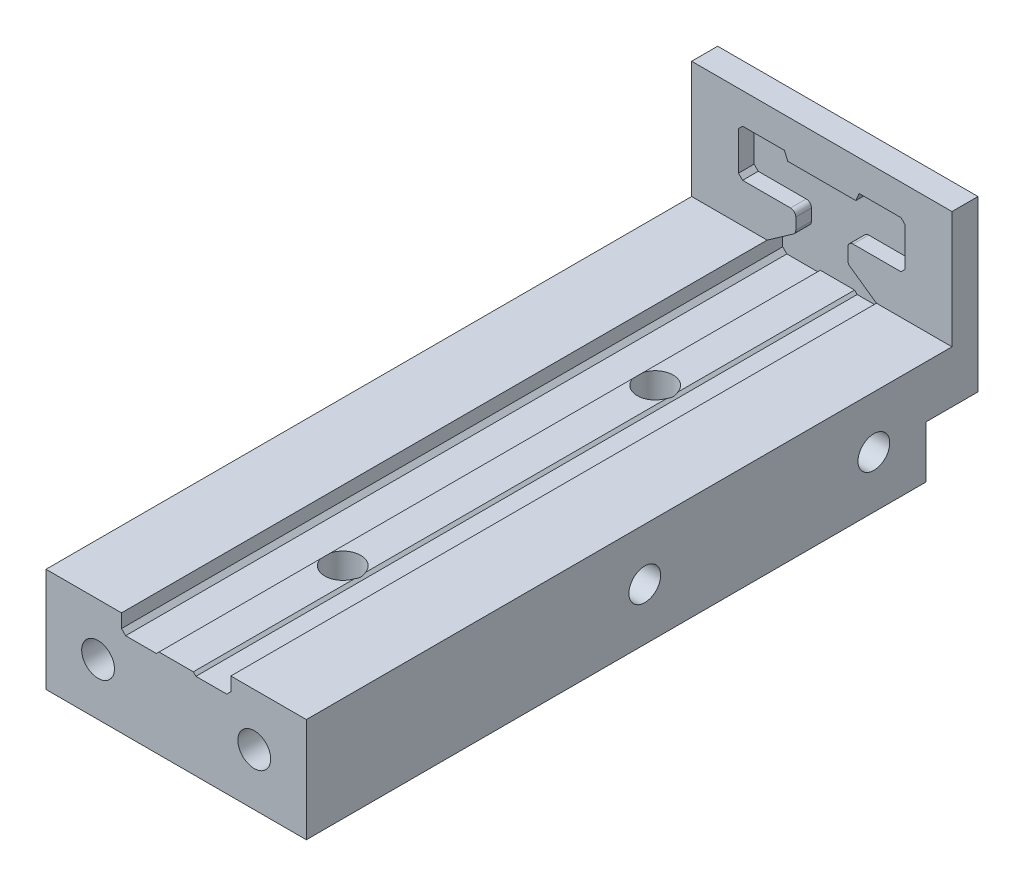
SolidWorks part; units mm, degrees
material "ABS"
ref_plane "Front Plane" through (0, 0, 0) normal (0, 0, 1) x (1, 0, 0)
ref_plane "Top Plane" through (0, 0, 0) normal (0, 1, 0) x (1, 0, 0)
ref_plane "Right Plane" through (0, 0, 0) normal (1, 0, 0) x (0, 0, -1)
sketch "Sketch1" plane through (0, 0, 0) normal (0, 0, 1) x (1, 0, 0)
  line L1 (-25, 10) -> (25, 10)
  line L2 (-25, 10) -> (-25, -10)
  line L3 (-25, -10) -> (25, -10)
  line L4 (25, 10) -> (25, -10)
  line L5 (-25, 10) -> (25, -10) construction
  line L6 (-25, -10) -> (25, 10) construction
  point P0 (0, 0)
  dimension "D1" = 50
  dimension "D2" = 20
extrude "Boss-Extrude1" add sketch "Sketch1" against normal blind 124
sketch "Sketch2" plane through (0, 0, 0) normal (0, 0, 1) x (1, 0, 0)
  line L29 (0, -10) -> (0, 10) construction
  line L30 (-25, -10) -> (25, -10) construction
  line L31 (25, 10) -> (-25, 10) construction
  line L43 (-9.9998, 9.7389) -> (9.9998, 9.7389) construction
  line L44 (-9.9998, 9.7389) -> (-9.9998, 7.5899) construction
  line L45 (-9.9998, 7.5899) -> (-9.4999, 7.09) construction
  line L46 (-9.4999, 7.09) -> (-3.9999, 7.09) construction
  line L47 (-3.9999, 7.09) -> (-3.5, 7.5899) construction
  line L48 (-3.5, 7.5899) -> (3.5, 7.5899) construction
  line L49 (-9.9998, 9.7389) -> (0, 9.7389) construction
  line L50 (9.9998, 9.7389) -> (0, 9.7389) construction
  line L51 (3.9999, 7.09) -> (3.5, 7.5899) construction
  line L52 (9.4999, 7.09) -> (3.9999, 7.09) construction
  line L53 (9.9998, 7.5899) -> (9.4999, 7.09) construction
  line L54 (9.9998, 9.7389) -> (9.9998, 7.5899) construction
  line L55 (-10.4998, 10.2389) -> (0, 10.2389)
  line L56 (10.4998, 10.2389) -> (0, 10.2389)
  line L57 (10.4998, 10.2389) -> (10.4998, 7.3828)
  line L58 (10.4998, 7.3828) -> (9.707, 6.59)
  line L59 (9.707, 6.59) -> (3.7928, 6.59)
  line L60 (3.7928, 6.59) -> (3.2929, 7.0899)
  line L61 (-3.2929, 7.0899) -> (3.2929, 7.0899)
  line L62 (-3.7928, 6.59) -> (-3.2929, 7.0899)
  line L63 (-9.707, 6.59) -> (-3.7928, 6.59)
  line L64 (-10.4998, 7.3828) -> (-9.707, 6.59)
  line L65 (-10.4998, 10.2389) -> (-10.4998, 7.3828)
  point P12 (0, 7.5899)
  dimension "D2" = 2.149
  dimension "D1" = 0.5
  dimension "D3" = 0.707
  dimension "D4" = 135
  dimension "D5" = 3.5
  dimension "D6" = 5.5
  dimension "D7" = 3.41
extrude "Cut-Extrude1" cut sketch "Sketch2" against normal up to next
sketch "Sketch4" plane through (0, 0, -124) normal (0, 0, -1) x (-1, 0, 0)
  line L0 (25, -10) -> (-25, -10) construction
  line L1 (25, -10) -> (-25, -10)
  line L2 (-25, -10) -> (-25, 32.5)
  line L3 (-25, 32.5) -> (25, 32.5)
  line L4 (25, 32.5) -> (25, -10)
  line L5 (-25, 10) -> (-10.4998, 10) construction
  dimension "D1" = 22.5
extrude "Boss-Extrude2" add sketch "Sketch4" along normal blind 5
sketch "Sketch5" plane through (0, 0, -124) normal (0, 0, 1) x (1, 0, 0)
  line L0 (0, 7.0899) -> (0, 32.5) construction
  line L1 (3.2929, 7.0899) -> (-3.2929, 7.0899) construction
  line L2 (-25, 32.5) -> (25, 32.5) construction
  line L3 (-3.5, 7.5899) -> (3.5, 7.5899) construction
  line L4 (3.5, 7.5899) -> (3.9999, 7.09) construction
  line L5 (3.9999, 7.09) -> (9.4999, 7.09) construction
  line L6 (9.4999, 7.09) -> (9.9998, 7.5899) construction
  line L7 (9.9998, 7.5899) -> (9.9998, 9.7389) construction
  line L8 (9.9998, 9.7389) -> (5.1396, 13.1421) construction
  line L9 (4.5, 14.3708) -> (4.5, 16.5898) construction
  line L10 (6, 18.0898) -> (15, 18.0898) construction
  line L11 (15, 18.0898) -> (15.4999, 18.5898) construction
  line L12 (15.4999, 18.5898) -> (15.4999, 25.5898) construction
  line L13 (15.4999, 25.5898) -> (15, 26.0897) construction
  line L14 (15, 26.0897) -> (7.5, 26.0897) construction
  line L15 (7.5, 26.0897) -> (6.8785, 24.5893) construction
  line L16 (6.8785, 24.5893) -> (-6.8785, 24.5893) construction
  line L17 (-7.5, 26.0897) -> (-6.8785, 24.5893) construction
  line L18 (-15, 26.0897) -> (-7.5, 26.0897) construction
  line L19 (-15.4999, 25.5898) -> (-15, 26.0897) construction
  line L20 (-15.4999, 18.5898) -> (-15.4999, 25.5898) construction
  line L21 (-15, 18.0898) -> (-15.4999, 18.5898) construction
  line L22 (-6, 18.0898) -> (-15, 18.0898) construction
  line L23 (-4.5, 14.3708) -> (-4.5, 16.5898) construction
  line L24 (-9.9998, 9.7389) -> (-5.1396, 13.1421) construction
  line L25 (-9.9998, 7.5899) -> (-9.9998, 9.7389) construction
  line L26 (-9.4999, 7.09) -> (-9.9998, 7.5899) construction
  line L27 (-3.9999, 7.09) -> (-9.4999, 7.09) construction
  line L28 (-3.5, 7.5899) -> (-3.9999, 7.09) construction
  line L29 (-3.2929, 7.0899) -> (3.2929, 7.0899)
  line L30 (3.2929, 7.0899) -> (3.7928, 6.59)
  line L31 (3.7928, 6.59) -> (9.707, 6.59)
  line L32 (9.707, 6.59) -> (10.4998, 7.3828)
  line L33 (10.4998, 7.3828) -> (10.4998, 9.9992)
  line L34 (10.4998, 9.9992) -> (5.4264, 13.5517)
  line L35 (5, 14.3708) -> (5, 16.5898)
  line L36 (6, 17.5898) -> (15.2071, 17.5898)
  line L37 (15.2071, 17.5898) -> (15.9999, 18.3826)
  line L38 (15.9999, 18.3826) -> (15.9999, 25.7969)
  line L39 (15.9999, 25.7969) -> (15.2071, 26.5897)
  line L40 (15.2071, 26.5897) -> (7.1659, 26.5897)
  line L41 (7.1659, 26.5897) -> (6.5444, 25.0893)
  line L42 (6.5444, 25.0893) -> (-6.5444, 25.0893)
  line L43 (-7.1659, 26.5897) -> (-6.5444, 25.0893)
  line L44 (-15.2071, 26.5897) -> (-7.1659, 26.5897)
  line L45 (-15.9999, 25.7969) -> (-15.2071, 26.5897)
  line L46 (-15.9999, 18.3826) -> (-15.9999, 25.7969)
  line L47 (-15.2071, 17.5898) -> (-15.9999, 18.3826)
  line L48 (-6, 17.5898) -> (-15.2071, 17.5898)
  line L49 (-5, 14.3708) -> (-5, 16.5898)
  line L50 (-10.4998, 9.9992) -> (-5.4264, 13.5517)
  line L51 (-10.4998, 7.3828) -> (-10.4998, 9.9992)
  line L52 (-9.707, 6.59) -> (-10.4998, 7.3828)
  line L53 (-3.7928, 6.59) -> (-9.707, 6.59)
  line L54 (-3.2929, 7.0899) -> (-3.7928, 6.59)
  arc A0 (6, 18.0898) -> (4.5, 16.5898) centre (6, 16.5898) ccw construction
  arc A1 (4.5, 14.3708) -> (5.1396, 13.1421) centre (6, 14.3708) ccw construction
  arc A2 (-4.5, 14.3708) -> (-5.1396, 13.1421) centre (-6, 14.3708) cw construction
  arc A3 (-6, 18.0898) -> (-4.5, 16.5898) centre (-6, 16.5898) cw construction
  arc A4 (5, 14.3708) -> (5.4264, 13.5517) centre (6, 14.3708) ccw
  arc A5 (6, 17.5898) -> (5, 16.5898) centre (6, 16.5898) ccw
  arc A6 (-6, 17.5898) -> (-5, 16.5898) centre (-6, 16.5898) cw
  arc A7 (-5, 14.3708) -> (-5.4264, 13.5517) centre (-6, 14.3708) cw
  point P33 (0, 24.5893)
  point P43 (0, 7.5899)
  dimension "D6" = 1.5
  dimension "D1" = 3.5
  dimension "D2" = 135
  dimension "D3" = 0.707
  dimension "D4" = 5.5
  dimension "D5" = 2.149
  dimension "D7" = 35
  dimension "D8" = 2.219
  dimension "D9" = 9
  dimension "D10" = 7
  dimension "D11" = 135
  dimension "D12" = 0.707
  dimension "D13" = 112.5
  dimension "D14" = 1.624
  dimension "D15" = 7.5
  dimension "D16" = 6.8785
  dimension "D17" = 0.5
extrude "Cut-Extrude2" cut sketch "Sketch5" against normal blind 3
sketch "Sketch6" plane through (0, 7.0899, 0) normal (0, 1, 0) x (1, 0, 0)
  line L0 (0, 127) -> (0, 0) construction
  line L1 (-3.2929, 127) -> (3.2929, 127) construction
  line L2 (-3.2929, 0) -> (3.2929, 0) construction
  circle A0 centre (0, 92) radius 3.45
  circle A1 centre (0, 32) radius 3.45
  dimension "D3" = 6.9
  dimension "D1" = 35
  dimension "D2" = 60
extrude "Cut-Extrude3" cut sketch "Sketch6" against normal through all
sketch "Sketch7" plane through (25, 0, 0) normal (1, 0, 0) x (0, 0, -1)
  line L0 (119, -10) -> (119, 0)
  line L1 (129, -10) -> (0, -10) construction
  line L2 (119, 0) -> (129, 0)
  line L3 (129, 32.5) -> (129, -10) construction
  line L4 (119, -10) -> (129, -10)
  line L5 (129, -10) -> (129, 0)
  dimension "D1" = 10
  dimension "D2" = 10
extrude "Cut-Extrude4" cut sketch "Sketch7" against normal through all
sketch "Sketch8" plane through (25, 0, 0) normal (1, 0, 0) x (0, 0, -1)
  line L1 (-0.0001, 0) -> (121, 0) construction
  line L2 (119, -10) -> (0, -10) construction
  line L3 (129, 32.5) -> (129, 0) construction
  circle A0 centre (109, 0) radius 3.05
  circle A2 centre (65, 0) radius 3.05
  dimension "D5" = 6.1
  dimension "D1" = 10
  dimension "D2" = 20
  dimension "D3" = 64
extrude "Cut-Extrude5" cut sketch "Sketch8" against normal blind 5
mirror "Mirror1" about plane through (0, 0, 0) normal (1, 0, 0) of "Cut-Extrude5"
sketch "Sketch9" plane through (0, 0, 0) normal (0, 0, 1) x (1, 0, 0)
  line L0 (-25, 0) -> (25, 0) construction
  line L1 (-25, 10) -> (-25, -10) construction
  line L2 (25, 10) -> (25, -10) construction
  line L4 (0, 7.0899) -> (0, -10) construction
  line L5 (-3.2929, 7.0899) -> (3.2929, 7.0899) construction
  line L6 (-25, -10) -> (25, -10) construction
  circle A0 centre (-15, 0) radius 3.15
  circle A1 centre (15, 0) radius 3.15
  dimension "D1" = 6.3
  dimension "D2" = 10
extrude "Cut-Extrude6" cut sketch "Sketch9" against normal blind 5
